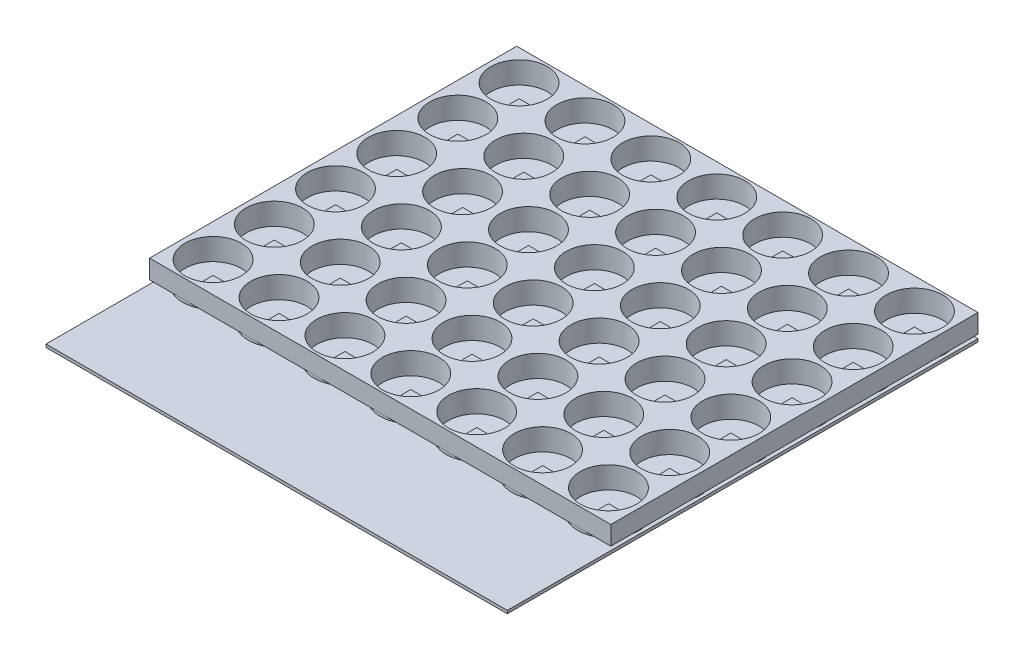
SolidWorks part; units mm, degrees
ref_plane "Ebene vorne" through (0, 0, 0) normal (0, 0, 1) x (1, 0, 0)
ref_plane "Ebene oben" through (0, 0, 0) normal (0, 1, 0) x (1, 0, 0)
ref_plane "Ebene rechts" through (0, 0, 0) normal (1, 0, 0) x (0, 0, -1)
sketch "Sketch1" plane through (0, 0, 0) normal (0, 1, 0) x (1, 0, 0)
  line L1 (122.5, 125) -> (-122.5, 125)
  line L2 (122.5, 125) -> (122.5, -125)
  line L3 (122.5, -125) -> (-122.5, -125)
  line L4 (-122.5, 125) -> (-122.5, -125)
  line L5 (122.5, 125) -> (-122.5, -125) construction
  line L6 (122.5, -125) -> (-122.5, 125) construction
  point P0 (0, 0)
  dimension "D1" = 250
  dimension "D2" = 245
extrude "Boss-Extrude1" add sketch "Sketch1" along normal blind 1.6
sketch "Sketch2" plane through (0, 1.6, 0) normal (0, 1, 0) x (1, 0, 0)
  line L0 (-122.5, 125) -> (-122.5, -125) construction
  line L1 (-107.7, 111.45) -> (-102.3, 111.45)
  line L2 (-107.7, 111.45) -> (-107.7, 106.05)
  line L3 (-107.7, 106.05) -> (-102.3, 106.05)
  line L4 (-102.3, 111.45) -> (-102.3, 106.05)
  line L5 (122.5, 125) -> (-122.5, 125) construction
  line L6 (-72.7, 111.45) -> (-67.3, 111.45)
  line L7 (-67.3, 111.45) -> (-67.3, 106.05)
  line L8 (-72.7, 106.05) -> (-67.3, 106.05)
  line L9 (-72.7, 111.45) -> (-72.7, 106.05)
  line L10 (-37.7, 111.45) -> (-32.3, 111.45)
  line L11 (-32.3, 111.45) -> (-32.3, 106.05)
  line L12 (-37.7, 106.05) -> (-32.3, 106.05)
  line L13 (-37.7, 111.45) -> (-37.7, 106.05)
  line L14 (-2.7, 111.45) -> (2.7, 111.45)
  line L15 (2.7, 111.45) -> (2.7, 106.05)
  line L16 (-2.7, 106.05) -> (2.7, 106.05)
  line L17 (-2.7, 111.45) -> (-2.7, 106.05)
  line L18 (32.3, 111.45) -> (37.7, 111.45)
  line L19 (37.7, 111.45) -> (37.7, 106.05)
  line L20 (32.3, 106.05) -> (37.7, 106.05)
  line L21 (32.3, 111.45) -> (32.3, 106.05)
  line L22 (67.3, 111.45) -> (72.7, 111.45)
  line L23 (72.7, 111.45) -> (72.7, 106.05)
  line L24 (67.3, 106.05) -> (72.7, 106.05)
  line L25 (67.3, 111.45) -> (67.3, 106.05)
  line L26 (102.3, 111.45) -> (107.7, 111.45)
  line L27 (107.7, 111.45) -> (107.7, 106.05)
  line L28 (102.3, 106.05) -> (107.7, 106.05)
  line L29 (102.3, 111.45) -> (102.3, 106.05)
  line L30 (-72.7, 78.95) -> (-67.3, 78.95)
  line L31 (-67.3, 78.95) -> (-67.3, 73.55)
  line L32 (-72.7, 73.55) -> (-67.3, 73.55)
  line L33 (-72.7, 78.95) -> (-72.7, 73.55)
  line L34 (-37.7, 78.95) -> (-32.3, 78.95)
  line L35 (-32.3, 78.95) -> (-32.3, 73.55)
  line L36 (-37.7, 73.55) -> (-32.3, 73.55)
  line L37 (-37.7, 78.95) -> (-37.7, 73.55)
  line L38 (-2.7, 78.95) -> (2.7, 78.95)
  line L39 (2.7, 78.95) -> (2.7, 73.55)
  line L40 (-2.7, 73.55) -> (2.7, 73.55)
  line L41 (-2.7, 78.95) -> (-2.7, 73.55)
  line L42 (32.3, 78.95) -> (37.7, 78.95)
  line L43 (37.7, 78.95) -> (37.7, 73.55)
  line L44 (32.3, 73.55) -> (37.7, 73.55)
  line L45 (32.3, 78.95) -> (32.3, 73.55)
  line L46 (67.3, 78.95) -> (72.7, 78.95)
  line L47 (72.7, 78.95) -> (72.7, 73.55)
  line L48 (67.3, 73.55) -> (72.7, 73.55)
  line L49 (67.3, 78.95) -> (67.3, 73.55)
  line L50 (102.3, 78.95) -> (107.7, 78.95)
  line L51 (107.7, 78.95) -> (107.7, 73.55)
  line L52 (102.3, 73.55) -> (107.7, 73.55)
  line L53 (102.3, 78.95) -> (102.3, 73.55)
  line L54 (-72.7, 46.45) -> (-67.3, 46.45)
  line L55 (-67.3, 46.45) -> (-67.3, 41.05)
  line L56 (-72.7, 41.05) -> (-67.3, 41.05)
  line L57 (-72.7, 46.45) -> (-72.7, 41.05)
  line L58 (-37.7, 46.45) -> (-32.3, 46.45)
  line L59 (-32.3, 46.45) -> (-32.3, 41.05)
  line L60 (-37.7, 41.05) -> (-32.3, 41.05)
  line L61 (-37.7, 46.45) -> (-37.7, 41.05)
  line L62 (-2.7, 46.45) -> (2.7, 46.45)
  line L63 (2.7, 46.45) -> (2.7, 41.05)
  line L64 (-2.7, 41.05) -> (2.7, 41.05)
  line L65 (-2.7, 46.45) -> (-2.7, 41.05)
  line L66 (32.3, 46.45) -> (37.7, 46.45)
  line L67 (37.7, 46.45) -> (37.7, 41.05)
  line L68 (32.3, 41.05) -> (37.7, 41.05)
  line L69 (32.3, 46.45) -> (32.3, 41.05)
  line L70 (67.3, 46.45) -> (72.7, 46.45)
  line L71 (72.7, 46.45) -> (72.7, 41.05)
  line L72 (67.3, 41.05) -> (72.7, 41.05)
  line L73 (67.3, 46.45) -> (67.3, 41.05)
  line L74 (102.3, 46.45) -> (107.7, 46.45)
  line L75 (107.7, 46.45) -> (107.7, 41.05)
  line L76 (102.3, 41.05) -> (107.7, 41.05)
  line L77 (102.3, 46.45) -> (102.3, 41.05)
  line L78 (-72.7, 13.95) -> (-67.3, 13.95)
  line L79 (-67.3, 13.95) -> (-67.3, 8.55)
  line L80 (-72.7, 8.55) -> (-67.3, 8.55)
  line L81 (-72.7, 13.95) -> (-72.7, 8.55)
  line L82 (-37.7, 13.95) -> (-32.3, 13.95)
  line L83 (-32.3, 13.95) -> (-32.3, 8.55)
  line L84 (-37.7, 8.55) -> (-32.3, 8.55)
  line L85 (-37.7, 13.95) -> (-37.7, 8.55)
  line L86 (-2.7, 13.95) -> (2.7, 13.95)
  line L87 (2.7, 13.95) -> (2.7, 8.55)
  line L88 (-2.7, 8.55) -> (2.7, 8.55)
  line L89 (-2.7, 13.95) -> (-2.7, 8.55)
  line L90 (32.3, 13.95) -> (37.7, 13.95)
  line L91 (37.7, 13.95) -> (37.7, 8.55)
  line L92 (32.3, 8.55) -> (37.7, 8.55)
  line L93 (32.3, 13.95) -> (32.3, 8.55)
  line L94 (67.3, 13.95) -> (72.7, 13.95)
  line L95 (72.7, 13.95) -> (72.7, 8.55)
  line L96 (67.3, 8.55) -> (72.7, 8.55)
  line L97 (67.3, 13.95) -> (67.3, 8.55)
  line L98 (102.3, 13.95) -> (107.7, 13.95)
  line L99 (107.7, 13.95) -> (107.7, 8.55)
  line L100 (102.3, 8.55) -> (107.7, 8.55)
  line L101 (102.3, 13.95) -> (102.3, 8.55)
  line L102 (-72.7, -18.55) -> (-67.3, -18.55)
  line L103 (-67.3, -18.55) -> (-67.3, -23.95)
  line L104 (-72.7, -23.95) -> (-67.3, -23.95)
  line L105 (-72.7, -18.55) -> (-72.7, -23.95)
  line L106 (-37.7, -18.55) -> (-32.3, -18.55)
  line L107 (-32.3, -18.55) -> (-32.3, -23.95)
  line L108 (-37.7, -23.95) -> (-32.3, -23.95)
  line L109 (-37.7, -18.55) -> (-37.7, -23.95)
  line L110 (-2.7, -18.55) -> (2.7, -18.55)
  line L111 (2.7, -18.55) -> (2.7, -23.95)
  line L112 (-2.7, -23.95) -> (2.7, -23.95)
  line L113 (-2.7, -18.55) -> (-2.7, -23.95)
  line L114 (32.3, -18.55) -> (37.7, -18.55)
  line L115 (37.7, -18.55) -> (37.7, -23.95)
  line L116 (32.3, -23.95) -> (37.7, -23.95)
  line L117 (32.3, -18.55) -> (32.3, -23.95)
  line L118 (67.3, -18.55) -> (72.7, -18.55)
  line L119 (72.7, -18.55) -> (72.7, -23.95)
  line L120 (67.3, -23.95) -> (72.7, -23.95)
  line L121 (67.3, -18.55) -> (67.3, -23.95)
  line L122 (102.3, -18.55) -> (107.7, -18.55)
  line L123 (107.7, -18.55) -> (107.7, -23.95)
  line L124 (102.3, -23.95) -> (107.7, -23.95)
  line L125 (102.3, -18.55) -> (102.3, -23.95)
  line L126 (-72.7, -51.05) -> (-67.3, -51.05)
  line L127 (-67.3, -51.05) -> (-67.3, -56.45)
  line L128 (-72.7, -56.45) -> (-67.3, -56.45)
  line L129 (-72.7, -51.05) -> (-72.7, -56.45)
  line L130 (-37.7, -51.05) -> (-32.3, -51.05)
  line L131 (-32.3, -51.05) -> (-32.3, -56.45)
  line L132 (-37.7, -56.45) -> (-32.3, -56.45)
  line L133 (-37.7, -51.05) -> (-37.7, -56.45)
  line L134 (-2.7, -51.05) -> (2.7, -51.05)
  line L135 (2.7, -51.05) -> (2.7, -56.45)
  line L136 (-2.7, -56.45) -> (2.7, -56.45)
  line L137 (-2.7, -51.05) -> (-2.7, -56.45)
  line L138 (32.3, -51.05) -> (37.7, -51.05)
  line L139 (37.7, -51.05) -> (37.7, -56.45)
  line L140 (32.3, -56.45) -> (37.7, -56.45)
  line L141 (32.3, -51.05) -> (32.3, -56.45)
  line L142 (67.3, -51.05) -> (72.7, -51.05)
  line L143 (72.7, -51.05) -> (72.7, -56.45)
  line L144 (67.3, -56.45) -> (72.7, -56.45)
  line L145 (67.3, -51.05) -> (67.3, -56.45)
  line L146 (102.3, -51.05) -> (107.7, -51.05)
  line L147 (107.7, -51.05) -> (107.7, -56.45)
  line L148 (102.3, -56.45) -> (107.7, -56.45)
  line L149 (102.3, -51.05) -> (102.3, -56.45)
  line L150 (-107.7, 78.95) -> (-102.3, 78.95)
  line L151 (-102.3, 78.95) -> (-102.3, 73.55)
  line L152 (-107.7, 73.55) -> (-102.3, 73.55)
  line L153 (-107.7, 78.95) -> (-107.7, 73.55)
  line L154 (-107.7, 46.45) -> (-102.3, 46.45)
  line L155 (-102.3, 46.45) -> (-102.3, 41.05)
  line L156 (-107.7, 41.05) -> (-102.3, 41.05)
  line L157 (-107.7, 46.45) -> (-107.7, 41.05)
  line L158 (-107.7, 13.95) -> (-102.3, 13.95)
  line L159 (-102.3, 13.95) -> (-102.3, 8.55)
  line L160 (-107.7, 8.55) -> (-102.3, 8.55)
  line L161 (-107.7, 13.95) -> (-107.7, 8.55)
  line L162 (-107.7, -18.55) -> (-102.3, -18.55)
  line L163 (-102.3, -18.55) -> (-102.3, -23.95)
  line L164 (-107.7, -23.95) -> (-102.3, -23.95)
  line L165 (-107.7, -18.55) -> (-107.7, -23.95)
  line L166 (-107.7, -51.05) -> (-102.3, -51.05)
  line L167 (-102.3, -51.05) -> (-102.3, -56.45)
  line L168 (-107.7, -56.45) -> (-102.3, -56.45)
  line L169 (-107.7, -51.05) -> (-107.7, -56.45)
  point P4 (-107.7, 108.75)
  point P7 (-105, 106.05)
  dimension "D1" = 5.4
  dimension "D2" = 16.25
  dimension "D3" = 17.5
  dimension "D4" = 7
  dimension "D5" = 6
extrude "Boss-Extrude2" add sketch "Sketch2" along normal blind 2
sketch "Sketch3" plane through (0, 3.6, 0) normal (0, 1, 0) x (1, 0, 0)
  line L0 (107.7, -51.05) -> (102.3, -51.05) construction
  line L1 (107.7, -56.45) -> (107.7, -51.05) construction
  line L3 (-122.5, 125) -> (122.5, 125)
  line L4 (-122.5, 125) -> (-122.5, -70)
  line L5 (-122.5, -70) -> (122.5, -70)
  line L6 (122.5, 125) -> (122.5, -70)
  circle A0 centre (105, -53.75) radius 15
  circle A1 centre (70, -53.75) radius 15
  circle A2 centre (35, -53.75) radius 15
  circle A3 centre (0, -53.75) radius 15
  circle A4 centre (-35, -53.75) radius 15
  circle A5 centre (-70, -53.75) radius 15
  circle A6 centre (-105, -53.75) radius 15
  circle A7 centre (70, -21.25) radius 15
  circle A8 centre (35, -21.25) radius 15
  circle A9 centre (0, -21.25) radius 15
  circle A10 centre (-35, -21.25) radius 15
  circle A11 centre (-70, -21.25) radius 15
  circle A12 centre (-105, -21.25) radius 15
  circle A13 centre (70, 11.25) radius 15
  circle A14 centre (35, 11.25) radius 15
  circle A15 centre (0, 11.25) radius 15
  circle A16 centre (-35, 11.25) radius 15
  circle A17 centre (-70, 11.25) radius 15
  circle A18 centre (-105, 11.25) radius 15
  circle A19 centre (70, 43.75) radius 15
  circle A20 centre (35, 43.75) radius 15
  circle A21 centre (0, 43.75) radius 15
  circle A22 centre (-35, 43.75) radius 15
  circle A23 centre (-70, 43.75) radius 15
  circle A24 centre (-105, 43.75) radius 15
  circle A25 centre (70, 76.25) radius 15
  circle A26 centre (35, 76.25) radius 15
  circle A27 centre (0, 76.25) radius 15
  circle A28 centre (-35, 76.25) radius 15
  circle A29 centre (-70, 76.25) radius 15
  circle A30 centre (-105, 76.25) radius 15
  circle A31 centre (70, 108.75) radius 15
  circle A32 centre (35, 108.75) radius 15
  circle A33 centre (0, 108.75) radius 15
  circle A34 centre (-35, 108.75) radius 15
  circle A35 centre (-70, 108.75) radius 15
  circle A36 centre (-105, 108.75) radius 15
  circle A37 centre (105, -21.25) radius 15
  circle A38 centre (105, 11.25) radius 15
  circle A39 centre (105, 43.75) radius 15
  circle A40 centre (105, 76.25) radius 15
  circle A41 centre (105, 108.75) radius 15
  point P5 (105, -51.05)
  point P9 (107.7, -53.75)
  point P94 (0, 0)
  point P95 (0, 0)
  dimension "D1" = 30
  dimension "D6" = 30
  dimension "D4" = 35
  dimension "D5" = 32.5
  dimension "D7" = 17.5
  dimension "D8" = 16.25
  dimension "D9" = 16.25
  dimension "D10" = 17.5
  dimension "D2" = 7
  dimension "D3" = 6
extrude "Boss-Extrude3" add sketch "Sketch3" along normal blind 10 separate body
sketch "Sketch4" plane through (0, 3.6, 0) normal (0, -1, 0) x (-1, 0, 0)
  circle A0 centre (105, 108.75) radius 16.2
  circle A1 centre (105, 108.75) radius 15 construction
  circle A2 centre (105, 108.75) radius 15
  circle A3 centre (105, 108.75) radius 15 construction
  circle A4 centre (70, 108.75) radius 15
  circle A5 centre (70, 108.75) radius 16.2
  circle A6 centre (35, 108.75) radius 15
  circle A7 centre (35, 108.75) radius 16.2
  circle A8 centre (0, 108.75) radius 15
  circle A9 centre (0, 108.75) radius 16.2
  circle A10 centre (-35, 108.75) radius 15
  circle A11 centre (-35, 108.75) radius 16.2
  circle A12 centre (-70, 108.75) radius 15
  circle A13 centre (-70, 108.75) radius 16.2
  circle A14 centre (-105, 108.75) radius 15
  circle A15 centre (-105, 108.75) radius 16.2
  circle A16 centre (70, 76.25) radius 15
  circle A17 centre (70, 76.25) radius 16.2
  circle A18 centre (35, 76.25) radius 15
  circle A19 centre (35, 76.25) radius 16.2
  circle A20 centre (0, 76.25) radius 15
  circle A21 centre (0, 76.25) radius 16.2
  circle A22 centre (-35, 76.25) radius 15
  circle A23 centre (-35, 76.25) radius 16.2
  circle A24 centre (-70, 76.25) radius 15
  circle A25 centre (-70, 76.25) radius 16.2
  circle A26 centre (-105, 76.25) radius 15
  circle A27 centre (-105, 76.25) radius 16.2
  circle A28 centre (70, 43.75) radius 15
  circle A29 centre (70, 43.75) radius 16.2
  circle A30 centre (35, 43.75) radius 15
  circle A31 centre (35, 43.75) radius 16.2
  circle A32 centre (0, 43.75) radius 15
  circle A33 centre (0, 43.75) radius 16.2
  circle A34 centre (-35, 43.75) radius 15
  circle A35 centre (-35, 43.75) radius 16.2
  circle A36 centre (-70, 43.75) radius 15
  circle A37 centre (-70, 43.75) radius 16.2
  circle A38 centre (-105, 43.75) radius 15
  circle A39 centre (-105, 43.75) radius 16.2
  circle A40 centre (70, 11.25) radius 15
  circle A41 centre (70, 11.25) radius 16.2
  circle A42 centre (35, 11.25) radius 15
  circle A43 centre (35, 11.25) radius 16.2
  circle A44 centre (0, 11.25) radius 15
  circle A45 centre (0, 11.25) radius 16.2
  circle A46 centre (-35, 11.25) radius 15
  circle A47 centre (-35, 11.25) radius 16.2
  circle A48 centre (-70, 11.25) radius 15
  circle A49 centre (-70, 11.25) radius 16.2
  circle A50 centre (-105, 11.25) radius 15
  circle A51 centre (-105, 11.25) radius 16.2
  circle A52 centre (70, -21.25) radius 15
  circle A53 centre (70, -21.25) radius 16.2
  circle A54 centre (35, -21.25) radius 15
  circle A55 centre (35, -21.25) radius 16.2
  circle A56 centre (0, -21.25) radius 15
  circle A57 centre (0, -21.25) radius 16.2
  circle A58 centre (-35, -21.25) radius 15
  circle A59 centre (-35, -21.25) radius 16.2
  circle A60 centre (-70, -21.25) radius 15
  circle A61 centre (-70, -21.25) radius 16.2
  circle A62 centre (-105, -21.25) radius 15
  circle A63 centre (-105, -21.25) radius 16.2
  circle A64 centre (70, -53.75) radius 15
  circle A65 centre (70, -53.75) radius 16.2
  circle A66 centre (35, -53.75) radius 15
  circle A67 centre (35, -53.75) radius 16.2
  circle A68 centre (0, -53.75) radius 15
  circle A69 centre (0, -53.75) radius 16.2
  circle A70 centre (-35, -53.75) radius 15
  circle A71 centre (-35, -53.75) radius 16.2
  circle A72 centre (-70, -53.75) radius 15
  circle A73 centre (-70, -53.75) radius 16.2
  circle A74 centre (-105, -53.75) radius 15
  circle A75 centre (-105, -53.75) radius 16.2
  circle A76 centre (105, 76.25) radius 15
  circle A77 centre (105, 76.25) radius 16.2
  circle A78 centre (105, 43.75) radius 15
  circle A79 centre (105, 43.75) radius 16.2
  circle A80 centre (105, 11.25) radius 15
  circle A81 centre (105, 11.25) radius 16.2
  circle A82 centre (105, -21.25) radius 15
  circle A83 centre (105, -21.25) radius 16.2
  circle A84 centre (105, -53.75) radius 15
  circle A85 centre (105, -53.75) radius 16.2
  dimension "D1" = 1.2
  dimension "D2" = 7
  dimension "D3" = 6
extrude "Boss-Extrude4" add sketch "Sketch4" along normal blind 1.6
